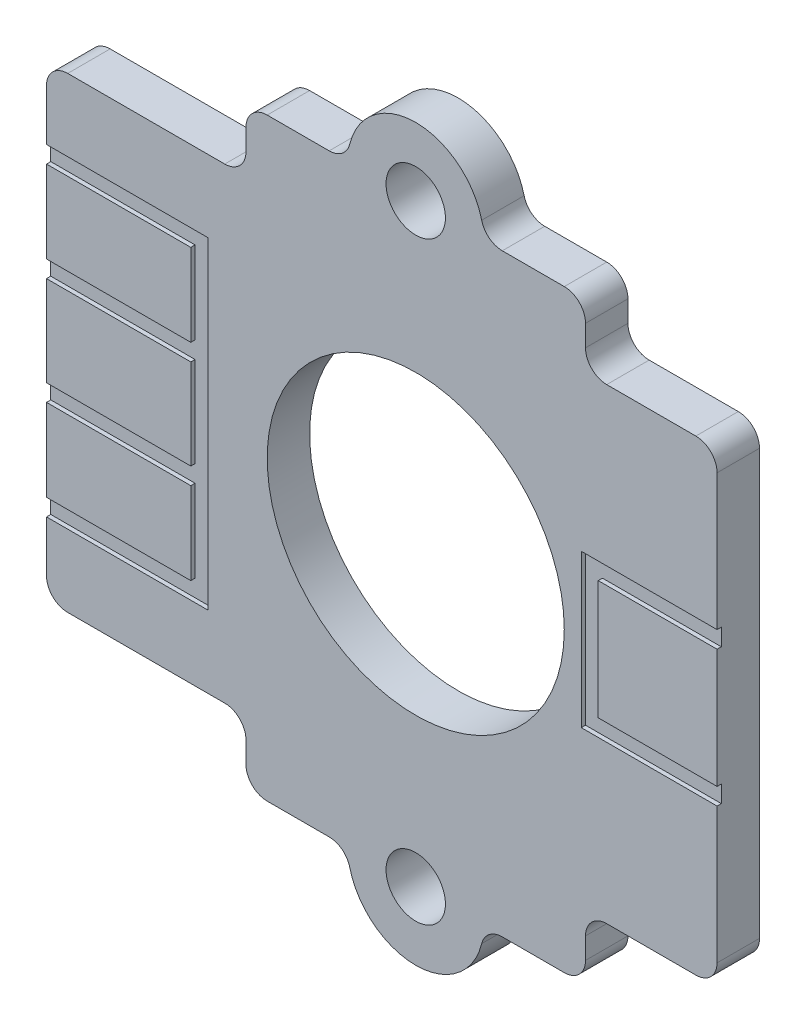
SolidWorks part; units mm, degrees
ref_plane "Спереди" through (0, 0, 0) normal (0, 0, 1) x (1, 0, 0)
ref_plane "Сверху" through (0, 0, 0) normal (0, 1, 0) x (1, 0, 0)
ref_plane "Справа" through (0, 0, 0) normal (1, 0, 0) x (0, 0, -1)
sketch "Model" plane through (0, 0, 0) normal (0, 0, 1) x (1, 0, 0)
  line L0 (-3.5, 7) -> (-2.0396, 7)
  line L2 (-3.5, -7) -> (-2.0396, -7)
  line L4 (-4, 6.5) -> (-4, 6)
  line L6 (4, 6.5) -> (4, 6)
  line L10 (-4, -6) -> (-4, -6.5)
  line L19 (4, -6) -> (4, -6.5)
  line L20 (2.0396, 7) -> (3.5, 7)
  line L24 (2.0396, -7) -> (3.5, -7)
  line L27 (0, 0) -> (0, 6.4277) construction
  line L28 (0, 0) -> (-4.4797, 0) construction
  line L29 (-8.7, 5) -> (-8.7, -5)
  line L30 (7.1, 5) -> (7.1, -5)
  line L31 (-8.2, 5.5) -> (-4.5, 5.5)
  line L32 (-8.2, -5.5) -> (-4.5, -5.5)
  line L36 (4.5, 5.5) -> (6.6, 5.5)
  line L39 (4.5, -5.5) -> (6.6, -5.5)
  arc A28 (-1.554, 7.381) -> (-2.0396, 7) centre (-2.0396, 7.5) cw
  arc A29 (2.0396, 7) -> (1.554, 7.381) centre (2.0396, 7.5) cw
  arc A30 (4.5, -5.5) -> (4, -6) centre (4.5, -6) ccw
  arc A31 (-3.5, 7) -> (-4, 6.5) centre (-3.5, 6.5) ccw
  arc A32 (-4.5, 5.5) -> (-4, 6) centre (-4.5, 6) ccw
  arc A34 (4, 6.5) -> (3.5, 7) centre (3.5, 6.5) ccw
  arc A35 (4.5, 5.5) -> (4, 6) centre (4.5, 6) cw
  circle A36 centre (0, 0) radius 3.5
  arc A37 (-8.2, 5.5) -> (-8.7, 5) centre (-8.2, 5) ccw
  arc A38 (-8.7, -5) -> (-8.2, -5.5) centre (-8.2, -5) ccw
  arc A39 (7.1, -5) -> (6.6, -5.5) centre (6.6, -5) cw
  arc A40 (6.6, 5.5) -> (7.1, 5) centre (6.6, 5) cw
  circle A41 centre (0, 0) radius 7 construction
  arc A42 (1.554, 7.381) -> (-1.554, 7.381) centre (0, 7) ccw
  circle A43 centre (0, 7) radius 0.7
  circle A44 centre (0, -7) radius 0.7
  arc A45 (-1.554, -7.381) -> (1.554, -7.381) centre (0, -7) ccw
  arc A46 (-4, -6) -> (-4.5, -5.5) centre (-4.5, -6) ccw
  arc A47 (-3.5, -7) -> (-4, -6.5) centre (-3.5, -6.5) cw
  arc A48 (-1.554, -7.381) -> (-2.0396, -7) centre (-2.0396, -7.5) ccw
  arc A49 (2.0396, -7) -> (1.554, -7.381) centre (2.0396, -7.5) ccw
  arc A50 (4, -6.5) -> (3.5, -7) centre (3.5, -6.5) cw
  point P13 (1.6, 7)
  point P20 (0, 0)
  point P74 (0, 7)
  point P75 (0, -7)
  dimension "D4" = 14
  dimension "D5" = 0.5
  dimension "D6" = 0.5
  dimension "D10" = 5.5
  dimension "D7" = 8
  dimension "D9" = 5.5
  dimension "D11" = 0.5
  dimension "D18" = 0.5
  dimension "D19" = 0.5
  dimension "D20" = 0.5
  dimension "D26" = 7
  dimension "D29" = 0.5
  dimension "D31" = 0.5
  dimension "D32" = 0.5
  dimension "D33" = 0.5
  dimension "D35" = 3.2
  dimension "D36" = 1.4
  dimension "D37" = 3.2
  dimension "D39" = 1.4
  dimension "D12" = 0.5
  dimension "D13" = 0.5
  dimension "D14" = 0.5
  dimension "D15" = 0.5
  dimension "D16" = 0.5
  dimension "D17" = 0.5
  dimension "D8" = 4
  dimension "D27" = 8.7
  dimension "D28" = 7.1
  dimension "D30" = 5.5
  dimension "D34" = 5.5
extrude "Бобышка-Вытянуть1" add sketch "Model" along normal mid plane 1
sketch "Sketch2" plane through (0, 0, 0.5) normal (0, 0, 1) x (1, 0, 0)
  line L9 (-5.1, 1.4625) -> (-10.1, 1.4625)
  line L18 (-5.1, 0) -> (-5.1, 3.6)
  line L19 (-5.1, 3.6) -> (-10.1, 3.6)
  line L20 (4.1, -1.6) -> (4.1, 1.6)
  line L21 (-5.1, 1.2625) -> (-10.1, 1.2625)
  line L34 (-4.9, 0.2) -> (-4.9, 3.8)
  line L35 (-4.9, 3.8) -> (-10.1, 3.8)
  line L36 (-5.1, 1.0625) -> (-10.1, 1.0625)
  line L38 (4.1, 1.6) -> (8.0158, 1.6)
  line L45 (-5.3, -0.2) -> (-5.3, 3.4)
  line L50 (4.1, -1.6) -> (8.0158, -1.6)
  line L56 (-5.3, 3.4) -> (-10.1, 3.4)
  line L57 (-5.3, 0.2) -> (-5.3, -3.4)
  line L58 (-4.9, -0.2) -> (-4.9, -3.8)
  line L59 (-5.1, 0) -> (-5.1, -3.6)
  line L60 (-5.3, -3.4) -> (-10.1, -3.4)
  line L61 (-5.1, -1.0625) -> (-10.1, -1.0625)
  line L62 (-4.9, -3.8) -> (-10.1, -3.8)
  line L63 (-5.1, -1.2625) -> (-10.1, -1.2625)
  line L64 (-5.1, -3.6) -> (-10.1, -3.6)
  line L65 (-5.1, -1.4625) -> (-10.1, -1.4625)
  line L66 (-9.5574, 5.6022) -> (-9.5574, -4.4906)
  line L67 (4.3, -1.4) -> (8.0158, -1.4)
  line L68 (0, 0) -> (7.1, 0) construction
  line L69 (0, 0.2) -> (7.1, 0.2) construction
  line L70 (0, -0.2) -> (7.1, -0.2) construction
  line L71 (4.3, -1.4) -> (4.3, 1.4)
  line L72 (4.3, 1.4) -> (8.0158, 1.4)
  line L73 (3.9, -1.8) -> (8.0158, -1.8)
  line L74 (3.9, -1.8) -> (3.9, 1.8)
  line L75 (3.9, 1.8) -> (8.0158, 1.8)
  line L76 (7.7397, 2.3128) -> (7.7397, -2.5375)
  line L77 (-4.9, 0.2) -> (-4.9, -0.2)
  line L79 (0, 0) -> (-5.1, 0) construction
  line L80 (0, -0.2) -> (-5.3, -0.2) construction
  line L81 (0, 0.2) -> (-4.9, 0.2) construction
  dimension "D1" = 0.2
  dimension "D2" = 0.2
  dimension "D3" = 3.6
  dimension "D4" = 4.1
  dimension "D5" = 5.1
  dimension "D6" = 3.2
  dimension "D7" = 0.2
  dimension "D8" = 0.2
extrude "Extrude2" cut sketch "Sketch2" against normal blind 0.1
